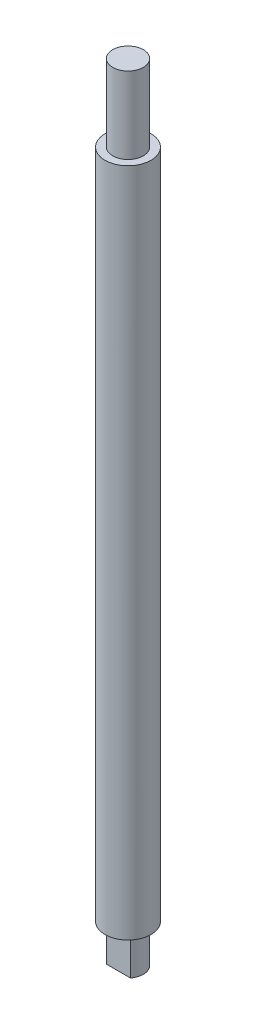
SolidWorks part; units mm, degrees
ref_plane "Спереди" through (0, 0, 0) normal (0, 0, 1) x (1, 0, 0)
ref_plane "Сверху" through (0, 0, 0) normal (0, 1, 0) x (1, 0, 0)
ref_plane "Справа" through (0, 0, 0) normal (1, 0, 0) x (0, 0, -1)
sketch "Эскиз1" plane through (0, 0, 0) normal (0, 1, 0) x (1, 0, 0)
  circle A0 centre (0, 0) radius 6
  dimension "D1" = 12
extrude "Бобышка-Вытянуть1" add sketch "Эскиз1" along normal blind 185
sketch "Эскиз2" plane through (0, 185, 0) normal (0, 1, 0) x (1, 0, 0)
  circle A0 centre (0, 0) radius 4
  dimension "D1" = 8
extrude "Бобышка-Вытянуть2" add sketch "Эскиз2" along normal blind 20
sketch "Эскиз3" plane through (0, 0, 0) normal (0, -1, 0) x (1, 0, 0)
  circle A0 centre (0, 0) radius 9.7324
  circle A1 centre (0, 0) radius 4
  dimension "D1" = 8
extrude "Вырез-Вытянуть1" cut sketch "Эскиз3" against normal blind 10
sketch "Эскиз4" plane through (0, 0, 0) normal (0, -1, 0) x (1, 0, 0)
  line L0 (-6, 0) -> (6, 0) construction
  line L1 (-4.4864, 2.5) -> (4.2655, 2.5)
  line L2 (0, 6) -> (0, -6) construction
  line L3 (4.2655, 2.5) -> (0, 5.3001)
  line L4 (0, 5.3001) -> (-4.4864, 2.5)
  circle A0 centre (0, 0) radius 6 construction
  dimension "D1" = 2.5
extrude "Вырез-Вытянуть2" cut sketch "Эскиз4" against normal blind 10
